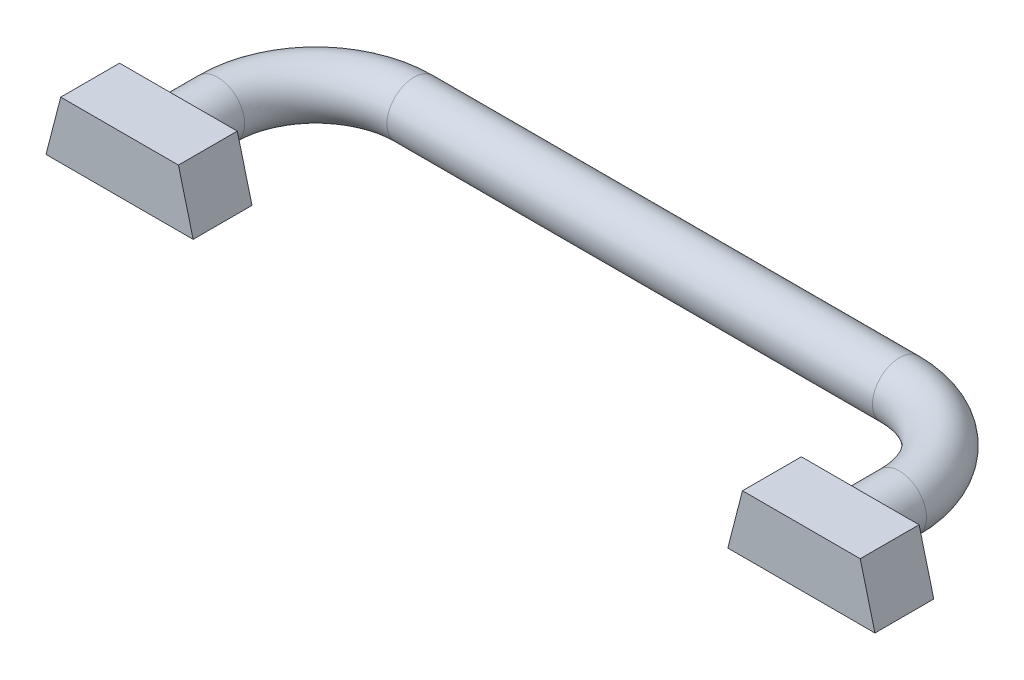
SolidWorks part; units mm, degrees
ref_plane "Спереди" through (0, 0, 0) normal (0, 0, 1) x (1, 0, 0)
ref_plane "Сверху" through (0, 0, 0) normal (0, 1, 0) x (1, 0, 0)
ref_plane "Справа" through (0, 0, 0) normal (1, 0, 0) x (0, 0, -1)
sketch "Эскиз1" plane through (0, 0, 0) normal (0, 1, 0) x (1, 0, 0)
  line L0 (0, 0) -> (0, 10)
  line L1 (10, 20) -> (59.5, 20)
  line L2 (69.5, 10) -> (69.5, 0)
  arc A0 (10, 20) -> (0, 10) centre (10, 10) ccw
  arc A1 (69.5, 10) -> (59.5, 20) centre (59.5, 10) ccw
  point P7 (0, 20)
  point P10 (69.5, 20)
  dimension "D4" = 10
  dimension "D5" = 10
  dimension "D1" = 20
  dimension "D2" = 69.5
  dimension "D3" = 20
sketch "Эскиз2" plane through (0, 0, 0) normal (0, 0, 1) x (1, 0, 0)
  circle A0 centre (0, 0) radius 2.75
  dimension "D1" = 5.5
sweep "По траектории1" add profiles "Эскиз2" path "Эскиз1"
sketch "Эскиз3" plane through (0, 0, 0) normal (0, 0, 1) x (1, 0, 0)
  line L0 (0, 0) -> (0, 6.3701) construction
  line L1 (-6, 3) -> (6, 3)
  line L2 (6, 3) -> (7.5, -2.8095)
  line L3 (7.5, -2.8095) -> (-7.5, -2.8095)
  line L4 (-7.5, -2.8095) -> (-6, 3)
  point P7 (0, 3)
  point P9 (0, -2.8095)
  dimension "D1" = 15
  dimension "D2" = 12
  dimension "D3" = 6
  dimension "D4" = 3
extrude "Бобышка-Вытянуть1" add sketch "Эскиз3" against normal blind 6
sketch "Эскиз4" plane through (0, 0, 0) normal (0, 0, 1) x (1, 0, 0)
  line L0 (69.5, 0) -> (69.5, 6.0342) construction
  line L1 (63.5, 3) -> (75.5, 3)
  line L2 (75.5, 3) -> (77, -2.8095)
  line L3 (77, -2.8095) -> (62, -2.8095)
  line L4 (62, -2.8095) -> (63.5, 3)
  point P7 (69.5, -2.8095)
  point P8 (69.5, 3)
  dimension "D1" = 3
  dimension "D2" = 12
  dimension "D3" = 15
  dimension "D4" = 6
extrude "Бобышка-Вытянуть2" add sketch "Эскиз4" against normal blind 6
